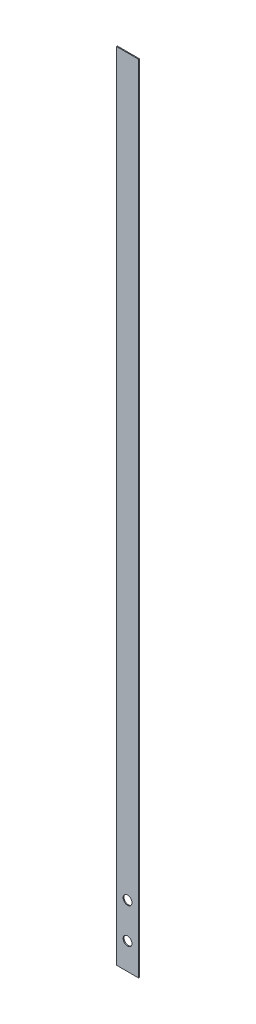
SolidWorks part; units mm, degrees
ref_plane "Front Plane" through (0, 0, 0) normal (0, 0, 1) x (1, 0, 0)
ref_plane "Top Plane" through (0, 0, 0) normal (0, 1, 0) x (1, 0, 0)
ref_plane "Right Plane" through (0, 0, 0) normal (1, 0, 0) x (0, 0, -1)
sketch "Sketch1" plane through (0, 0, 0) normal (0, 1, 0) x (1, 0, 0)
  line L1 (-2.5, 0.1) -> (2.5, 0.1)
  line L2 (-2.5, 0.1) -> (-2.5, -0.1)
  line L3 (-2.5, -0.1) -> (2.5, -0.1)
  line L4 (2.5, 0.1) -> (2.5, -0.1)
  line L5 (-2.5, 0.1) -> (2.5, -0.1) construction
  line L6 (-2.5, -0.1) -> (2.5, 0.1) construction
  point P0 (0, 0)
  dimension "D1" = 5
  dimension "D2" = 0.2
extrude "Boss-Extrude1" add sketch "Sketch1" along normal blind 180
sketch "Sketch2" plane through (0, 0, -0.1) normal (0, 0, -1) x (-1, 0, 0)
  line L0 (-2.5, 0) -> (2.5, 0) construction
  line L1 (2.5, 180) -> (2.5, 0) construction
  circle A0 centre (0, 6) radius 1
  circle A1 centre (0, 14) radius 1
  dimension "D1" = 2
  dimension "D2" = 2
  dimension "D3" = 6
  dimension "D4" = 8
  dimension "D5" = 2.5
extrude "Cut-Extrude1" cut sketch "Sketch2" against normal through all
